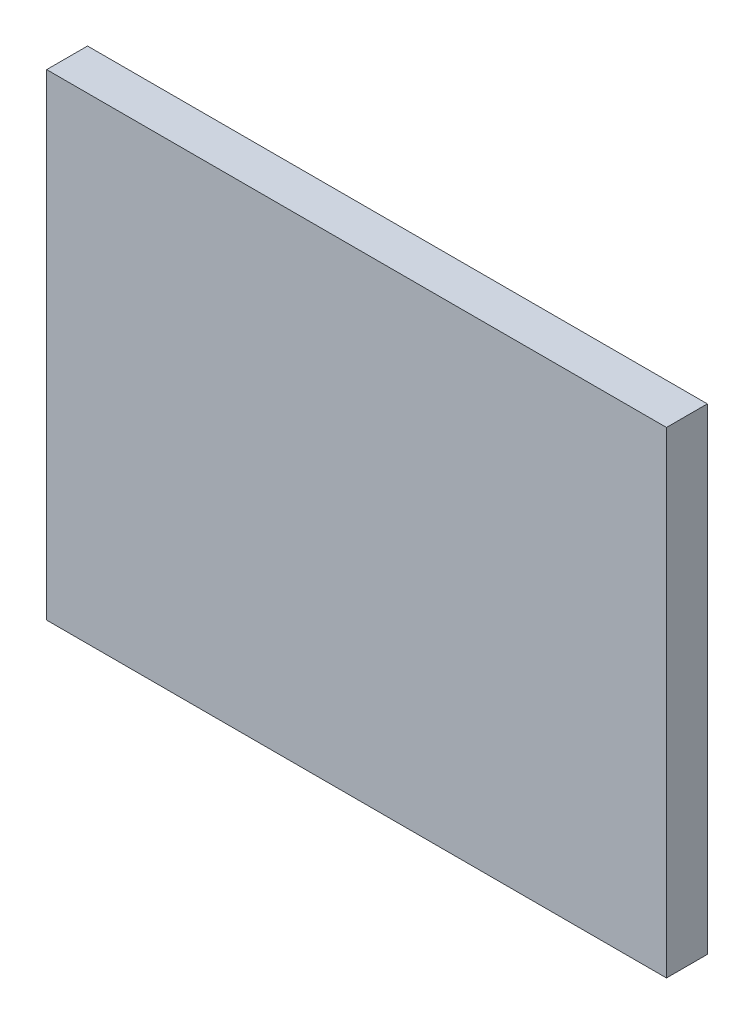
SolidWorks part; units mm, degrees
ref_plane "Front Plane" through (0, 0, 0) normal (0, 0, 1) x (1, 0, 0)
ref_plane "Top Plane" through (0, 0, 0) normal (0, 1, 0) x (1, 0, 0)
ref_plane "Right Plane" through (0, 0, 0) normal (1, 0, 0) x (0, 0, -1)
sketch "Sketch1" plane through (0, 0, 0) normal (0, 1, 0) x (1, 0, 0)
  line L1 (-45.5, -3) -> (45.5, -3)
  line L2 (-45.5, -3) -> (-45.5, 3)
  line L3 (-45.5, 3) -> (45.5, 3)
  line L4 (45.5, -3) -> (45.5, 3)
  line L5 (-45.5, -3) -> (45.5, 3) construction
  line L6 (-45.5, 3) -> (45.5, -3) construction
  point P0 (0, 0)
  dimension "D1" = 6
  dimension "D2" = 91
extrude "Boss-Extrude1" add sketch "Sketch1" along normal blind 70
